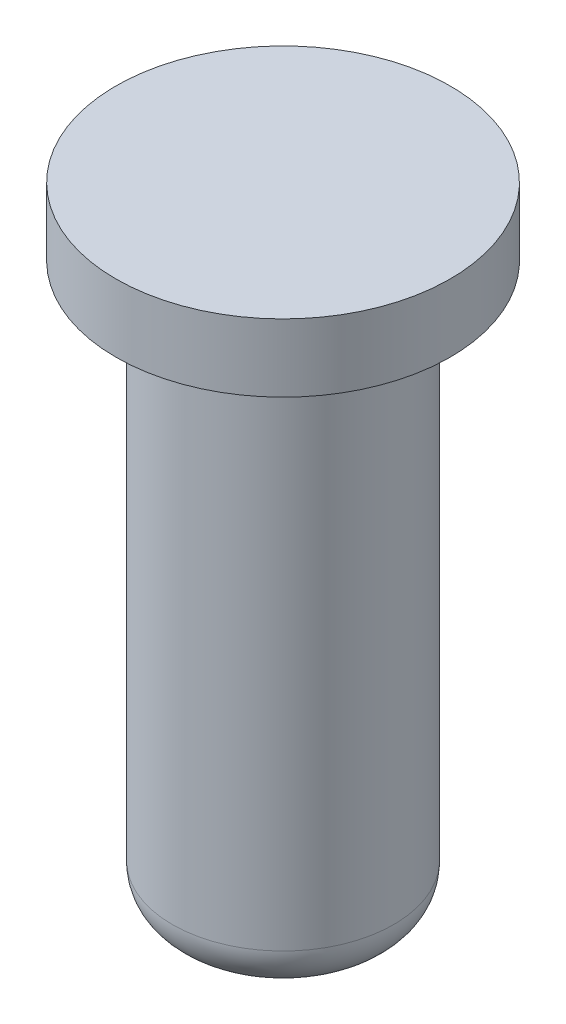
SolidWorks part; units mm, degrees
ref_plane "Front Plane" through (0, 0, 0) normal (0, 0, 1) x (1, 0, 0)
ref_plane "Top Plane" through (0, 0, 0) normal (0, 1, 0) x (1, 0, 0)
ref_plane "Right Plane" through (0, 0, 0) normal (1, 0, 0) x (0, 0, -1)
sketch "Sketch1" plane through (0, 0, 0) normal (0, 1, 0) x (1, 0, 0)
  circle A0 centre (0, 0) radius 4.9
  dimension "D1" = 9.8
extrude "Boss-Extrude1" add sketch "Sketch1" along normal blind 25
sketch "Sketch2" plane through (0, 25, 0) normal (0, 1, 0) x (1, 0, 0)
  circle A2 centre (0, 0) radius 7.4
  circle A3 centre (0, 0) radius 7.4
  dimension "D1" = 2.5
extrude "Boss-Extrude2" add sketch "Sketch2" along normal blind 3
fillet "Fillet1" radius 2 1 edges at (0, 0, 4.9)
